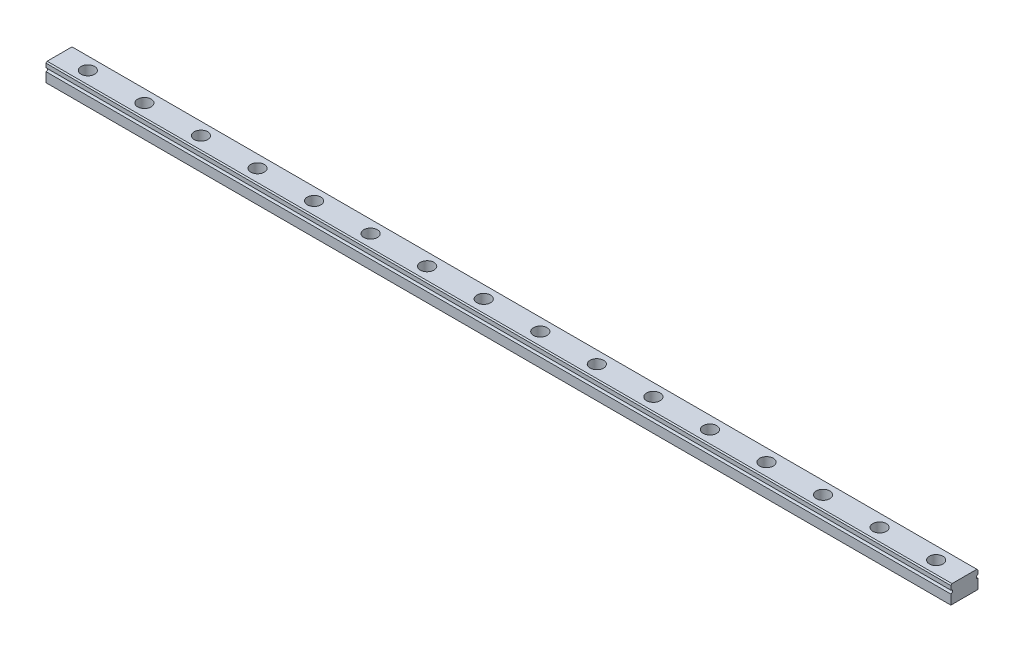
SolidWorks part; units mm, degrees
material "1.4301 (X5CrNi18-10)"
ref_plane "Ebene vorne" through (0, 0, 0) normal (0, 0, 1) x (1, 0, 0)
ref_plane "Ebene oben" through (0, 0, 0) normal (0, 1, 0) x (1, 0, 0)
ref_plane "Ebene rechts" through (0, 0, 0) normal (1, 0, 0) x (0, 0, -1)
sketch "Skizze1" plane through (0, 0, 0) normal (1, 0, 0) x (0, 0, -1)
  line L0 (-6, 1) -> (6, 1) construction
  line L1 (6, -4) -> (-6, -4)
  line L2 (6, -4) -> (6, 0.25)
  line L3 (6, 4) -> (-6, 4)
  line L4 (-6, -4) -> (-6, 0.25)
  line L5 (6, -4) -> (-6, 4) construction
  line L6 (6, 4) -> (-6, -4) construction
  line L7 (-6, 1.75) -> (-6, 4)
  line L8 (6, 1.75) -> (6, 4)
  arc A0 (-6, 0.25) -> (-6, 1.75) centre (-6, 1) ccw
  arc A1 (6, 1.75) -> (6, 0.25) centre (6, 1) ccw
  point P0 (0, 0)
  point P16 (-5.25, 1)
  dimension "D5" = 0.75
  dimension "D1" = 12
  dimension "D2" = 8
  dimension "D3" = 3
  dimension "D4" = 0.75
extrude "Aufsatz-Linear austragen1" add sketch "Skizze1" along normal blind 400
chamfer "Fase1" distance 0.5 angle 45 2 edges at (200, 4, -6) (200, 4, 6)
sketch "Skizze2" plane through (0, 4, 0) normal (0, 1, 0) x (1, 0, 0)
  line L0 (400, 0) -> (0, 0) construction
  line L1 (400, 5.5) -> (400, -5.5) construction
  line L2 (0, 5.5) -> (0, -5.5) construction
  line L3 (12.5, 0) -> (37.5, 0) construction
  point P13 (12.5, 0)
  point P15 (37.5, 0)
  point P16 (62.5, 0)
  point P17 (87.5, 0)
  point P18 (112.5, 0)
  point P19 (137.5, 0)
  point P20 (162.5, 0)
  point P21 (187.5, 0)
  point P22 (212.5, 0)
  point P23 (237.5, 0)
  point P24 (262.5, 0)
  point P25 (287.5, 0)
  point P26 (312.5, 0)
  point P27 (337.5, 0)
  point P28 (362.5, 0)
  point P29 (387.5, 0)
  dimension "D3" = 25
  dimension "D1" = 12.5
  dimension "D2" = 16
hole_wizard "Stirnsenkung für M3 Dünnkopf-Zylinderschraube mit Innensechskant1" positions "3D-Skizze1" profile "Skizze3" counterbore size "M3" standard "DIN" end condition through all
sketch3d "3D-Skizze1"
  line L0 (0, 4, 0) -> (400, 4, 0) construction
  line L1 (0, 4, -5.5) -> (0, 4, 5.5) construction
  line L2 (400, 4, -5.5) -> (400, 4, 5.5) construction
  point P26 (387.5, 4, 0)
  point P28 (362.5, 4, 0)
  point P30 (337.5, 4, 0)
  point P32 (312.5, 4, 0)
  point P34 (287.5, 4, 0)
  point P36 (262.5, 4, 0)
  point P38 (237.5, 4, 0)
  point P40 (212.5, 4, 0)
  point P42 (187.5, 4, 0)
  point P44 (162.5, 4, 0)
  point P46 (137.5, 4, 0)
  point P48 (112.5, 4, 0)
  point P50 (87.5, 4, 0)
  point P52 (62.5, 4, 0)
  point P54 (37.5, 4, 0)
  point P56 (12.5, 4, 0)
sketch "Skizze3" plane through (12.5, 4, 0) normal (1, 0, 0) x (0, 0, 1)
  line L0 (0, 0) -> (0, 8)
  line L1 (0, 8) -> (2, 8)
  line L3 (2, 8) -> (2, 5)
  line L4 (2, 5) -> (3, 5)
  line L5 (3, 5) -> (3, 0)
  line L7 (3, 0) -> (0, 0)
  line L11 (0, -6.35) -> (0, 107.95) construction
  dimension "Bohrerdurchmesser" = 4
  dimension "Bohrungstiefe" = 8
  dimension "Senkdurchmesser2" = 6
  dimension "Senktiefe2" = 5
ref_plane "Mitte Schiene" through (200, 0, 0) normal (1, 0, 0) x (0, 0, -1)
equation "\"D4@Skizze1\"=\"D5@Skizze1\""
